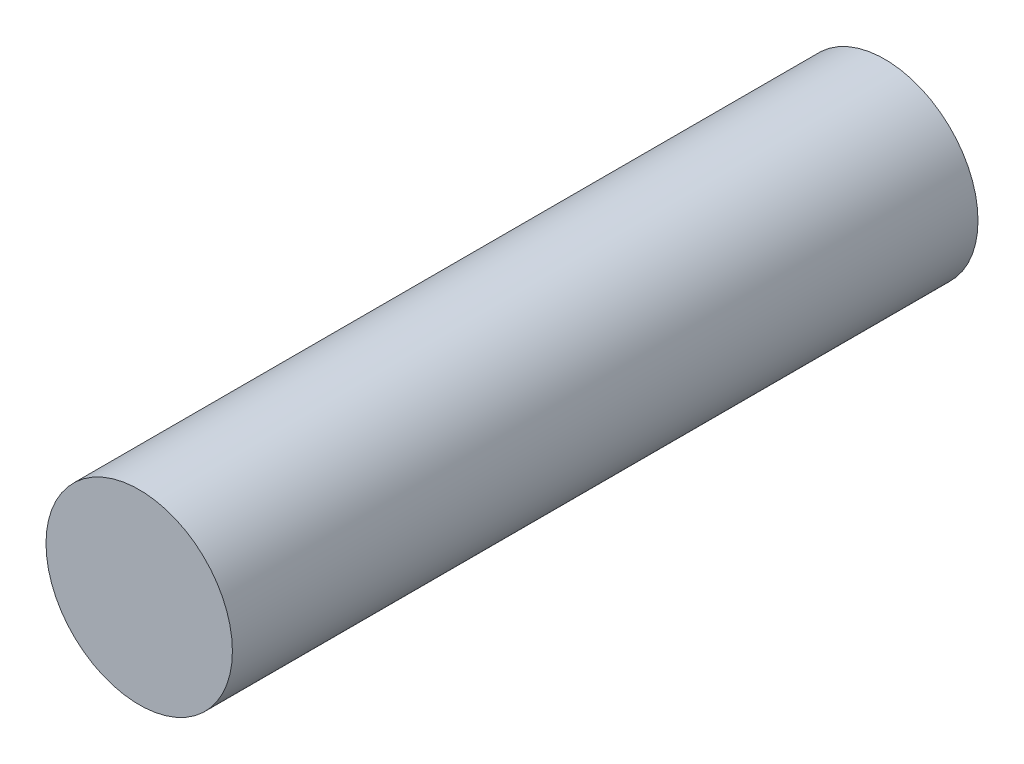
SolidWorks part; units mm, degrees
ref_plane "Piano frontale" through (0, 0, 0) normal (0, 0, 1) x (1, 0, 0)
ref_plane "Piano superiore" through (0, 0, 0) normal (0, 1, 0) x (1, 0, 0)
ref_plane "Piano destro" through (0, 0, 0) normal (1, 0, 0) x (0, 0, -1)
sketch "Schizzo1" plane through (0, 0, 0) normal (0, 0, 1) x (1, 0, 0)
  circle A0 centre (0, 0) radius 3
  dimension "D1" = 6
extrude "Estrusione-Estrusione1" add sketch "Schizzo1" against normal blind 24
